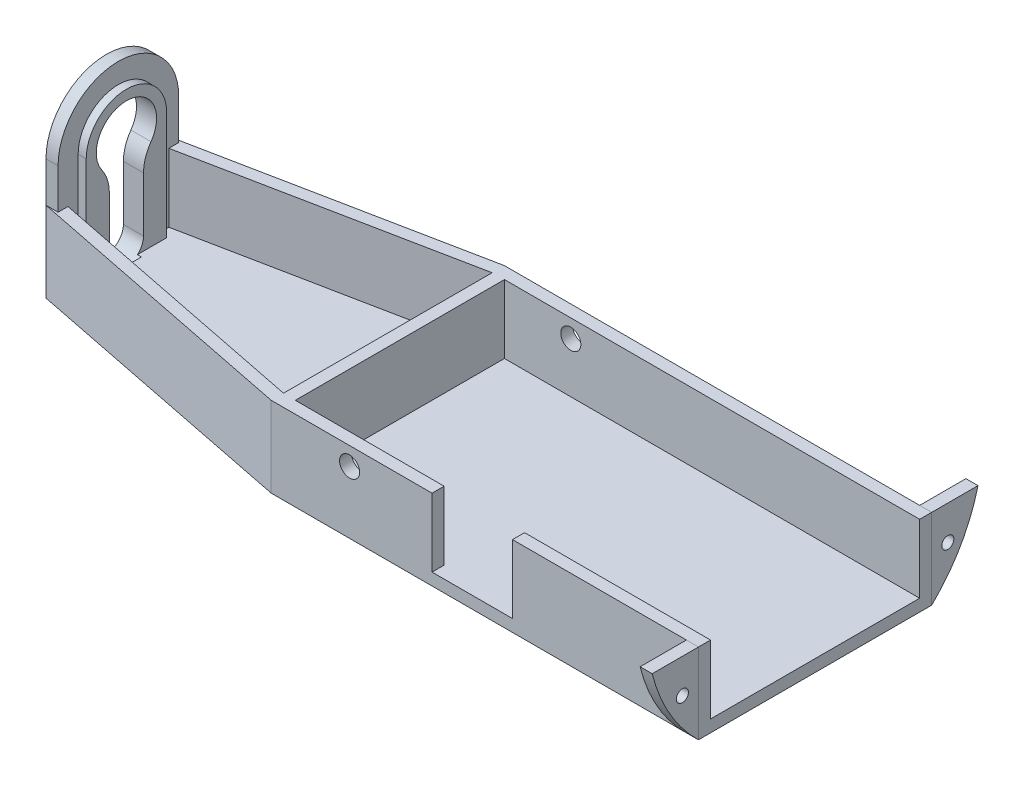
SolidWorks part; units mm, degrees
ref_plane "Front Plane" through (0, 0, 0) normal (0, 0, 1) x (1, 0, 0)
ref_plane "Top Plane" through (0, 0, 0) normal (0, 1, 0) x (1, 0, 0)
ref_plane "Right Plane" through (0, 0, 0) normal (1, 0, 0) x (0, 0, -1)
sketch "Sketch2" plane through (0, 0, 0) normal (0, 1, 0) x (1, 0, 0)
  line L0 (-119.25, 15) -> (-119.25, -15)
  line L1 (-49.25, -29) -> (57, -29)
  line L2 (-49.25, -29) -> (-49.25, 29)
  line L3 (-49.25, 29) -> (57, 29)
  line L4 (57, -29) -> (57, 29)
  line L6 (60, 12) -> (60, -39) construction
  line L7 (-119.25, -15) -> (-49.25, -29)
  line L8 (-119.25, 15) -> (-49.25, 29)
  line L9 (-46.25, -23.4) -> (-46.25, 23.4) construction
  line L10 (-46.25, 23.4) -> (-46.25, -23.4) construction
  point P0 (0, 0)
  point P8 (-49.25, 0)
  point P9 (-119.25, 0)
  point P14 (-46.25, 0)
  dimension "D1" = 3
  dimension "D2" = 58
  dimension "D3" = 30
  dimension "D4" = 70
  dimension "D5" = 3
extrude "Boss-Extrude1" add sketch "Sketch2" along normal blind 3 contours L8 L0 L7 L2 | L1 L4 L3 L2
sketch "Sketch3" plane through (0, 0, 0) normal (0, -1, 0) x (1, 0, 0)
  line L0 (-49.25, -29) -> (57, -29) construction
  line L1 (-49.25, 29) -> (-46.25, 29)
  line L2 (-49.25, 29) -> (-49.25, -29)
  line L3 (-49.25, -29) -> (-46.25, -29)
  line L4 (-46.25, 29) -> (-46.25, -29)
  line L5 (57, 29) -> (57, -29) construction
  line L6 (-46.25, 29) -> (57, 29)
  line L7 (-46.25, 29) -> (-46.25, 26)
  line L8 (-46.25, 26) -> (57, 26)
  line L9 (57, 29) -> (57, 26)
  line L10 (-119.25, 15) -> (-49.25, 29) construction
  line L11 (57, -29) -> (-46.25, -29)
  line L12 (57, -29) -> (57, -26)
  line L13 (57, -26) -> (-46.25, -26)
  line L14 (-46.25, -29) -> (-46.25, -26)
  line L15 (-119.25, -11.9406) -> (-49.25, -25.9406)
  line L16 (-119.25, -15) -> (-49.25, -29) construction
  line L17 (-119.25, -15) -> (-119.25, 15) construction
  line L18 (-119.25, 11.9406) -> (-119.25, 15)
  line L19 (-119.25, 15) -> (-49.25, 29)
  line L20 (-49.25, 29) -> (-49.25, 25.9406)
  line L21 (-119.25, -11.9406) -> (-119.25, -15)
  line L22 (-119.25, -15) -> (-49.25, -29)
  line L23 (-49.25, -25.9406) -> (-49.25, -29)
  line L29 (-119.25, 11.9406) -> (-49.25, 25.9406)
  line M3 (-49.25, -29) -> (57, -29)
  line M4 (57, -29) -> (57, 29)
  line M5 (57, 29) -> (-49.25, 29)
  dimension "D1" = 3
  dimension "D2" = 3
  dimension "D3" = 3
  dimension "D4" = 3
  dimension "D5" = 3
extrude "Boss-Extrude2" add sketch "Sketch3" against normal blind 20 contours L4 L8 M4 M5 | L4 L2 M5 M3 | L13 L4 M4 M3
sketch "Sketch4" plane through (0, 0, 0) normal (0, -1, 0) x (1, 0, 0)
  line L0 (-119.25, -15) -> (-119.25, 15)
  line L1 (-119.25, -15) -> (-116.25, -15)
  line L2 (-119.25, 15) -> (-116.25, 15)
  line L3 (-116.25, -15) -> (-116.25, 15)
  dimension "D1" = 3
extrude "Boss-Extrude3" add sketch "Sketch4" against normal blind 30
sketch "Sketch5" plane through (0, 3, 0) normal (0, 1, 0) x (1, 0, 0)
  line L0 (-49.25, 25.9406) -> (-116.25, 12.5406)
  line L1 (-49.25, 29) -> (-49.25, -29) construction
  line L2 (-116.25, -15) -> (-116.25, 15) construction
  line L3 (-116.25, 12.5406) -> (-119.25, 15)
  line L4 (-119.25, 15) -> (-49.25, 29)
  line L5 (-49.25, 29) -> (-49.25, 25.9406)
  line L6 (-49.25, -25.9406) -> (-116.25, -12.5406)
  line L7 (-116.25, -12.5406) -> (-119.25, -15)
  line L8 (-119.25, -15) -> (-49.25, -29)
  line L9 (-49.25, -29) -> (-49.25, -25.9406)
  dimension "D1" = 3
  dimension "D2" = 3
extrude "Boss-Extrude4" add sketch "Sketch5" along normal up to surface (17 mm away) up to face at (4.625, 20, 0)
sketch "Sketch6" plane through (-119.25, 0, 0) normal (-1, 0, 0) x (0, 0, 1)
  line L0 (15, 30) -> (-15, 30) construction
  circle A0 centre (0, 30) radius 15
extrude "Boss-Extrude5" add sketch "Sketch6" against normal up to surface (3 mm away) up to face at (-116.25, 18.25, 0)
sketch "Sketch7" plane through (-119.25, 0, 0) normal (-1, 0, 0) x (0, 0, 1)
  circle A0 centre (0, 30) radius 3.1
  point P3 (0, 0)
  point P21 (0, 30)
  dimension "D1" = 6.2
sketch "Sketch19" plane through (-116.25, 0, 0) normal (1, 0, 0) x (0, 0, -1)
  line L0 (15, 0) -> (-15, 0) construction
  line L1 (-10, 30) -> (-10, 0)
  line L2 (10, 30) -> (10, 0)
  line L3 (-10, 0) -> (10, 0)
  arc A0 (10, 30) -> (-10, 30) centre (0, 30) ccw
  circle A1 centre (0, 30) radius 1.5
  point P9 (0, 0)
  point P10 (0, 0)
  point P11 (0, 0)
  dimension "D1" = 20
  dimension "D2" = 3
extrude "Boss-Extrude9" add sketch "Sketch19" along normal blind 2
sketch "Sketch10" plane through (0, 0, 29) normal (0, 0, 1) x (1, 0, 0)
  circle A0 centre (-29.75, 15.5) radius 2.5
  dimension "D1" = 5
extrude "Cut-Extrude3" cut sketch "Sketch10" against normal through all both and the other way through all
sketch "Sketch16" plane through (57, 0, 0) normal (1, 0, 0) x (0, 0, -1)
  line L0 (-29, 20) -> (-40.5093, 20)
  line L1 (-29, 0) -> (-29, 20)
  line L2 (29, 20) -> (40.5093, 20)
  line L3 (29, 0) -> (29, 20)
  arc A0 (-40.5093, 20) -> (-29, 0) centre (0, 30) ccw
  circle A1 centre (-33, 11.5) radius 1.5 construction
  arc A2 (29, 0) -> (40.5093, 20) centre (0, 30) ccw
  circle A3 centre (-33, 11.5) radius 1.5
  circle A5 centre (33, 11.5) radius 1.5
  circle A7 centre (33, 11.5) radius 1.5 construction
extrude "Boss-Extrude8" add sketch "Sketch16" against normal blind 3 separate body
sketch "Sketch18" plane through (0, 0, 29) normal (0, 0, 1) x (1, 0, 0)
  line L0 (57, 20) -> (-49.25, 20) construction
  line L1 (10.75, 20) -> (-9.25, 20)
  line L2 (10.75, 20) -> (10.75, 3)
  line L3 (10.75, 3) -> (-9.25, 3)
  line L4 (-9.25, 20) -> (-9.25, 3)
  line L5 (10.75, 5.4) -> (10.75, 17.4) construction
  line L6 (-49.25, 0) -> (57, 0) construction
  dimension "D1" = 20
  dimension "D2" = 3
extrude "Cut-Extrude5" cut sketch "Sketch18" against normal up to next (3 mm away)
sketch "Sketch20" plane through (-119.25, 0, 0) normal (-1, 0, 0) x (0, 0, 1)
  line L0 (0, 30) -> (0, 6.25)
  line L1 (-4.25, 30) -> (-4.25, 6.25)
  line L2 (4.25, 30) -> (4.25, 6.25)
  circle A0 centre (0, 30) radius 7.5
  arc A1 (-4.25, 30) -> (4.25, 30) centre (0, 30) cw
  arc A2 (-4.25, 6.25) -> (4.25, 6.25) centre (0, 6.25) ccw
  dimension "D1" = 15
  dimension "D4" = 23.75
  dimension "D2" = 4.25
  dimension "D3" = 4.25
extrude "Cut-Extrude6" cut sketch "Sketch20" against normal blind 6
fillet "Fillet1" radius 10 2 edges at (-116.75, 23.8204, 4.25) (-116.75, 23.8204, -4.25)
